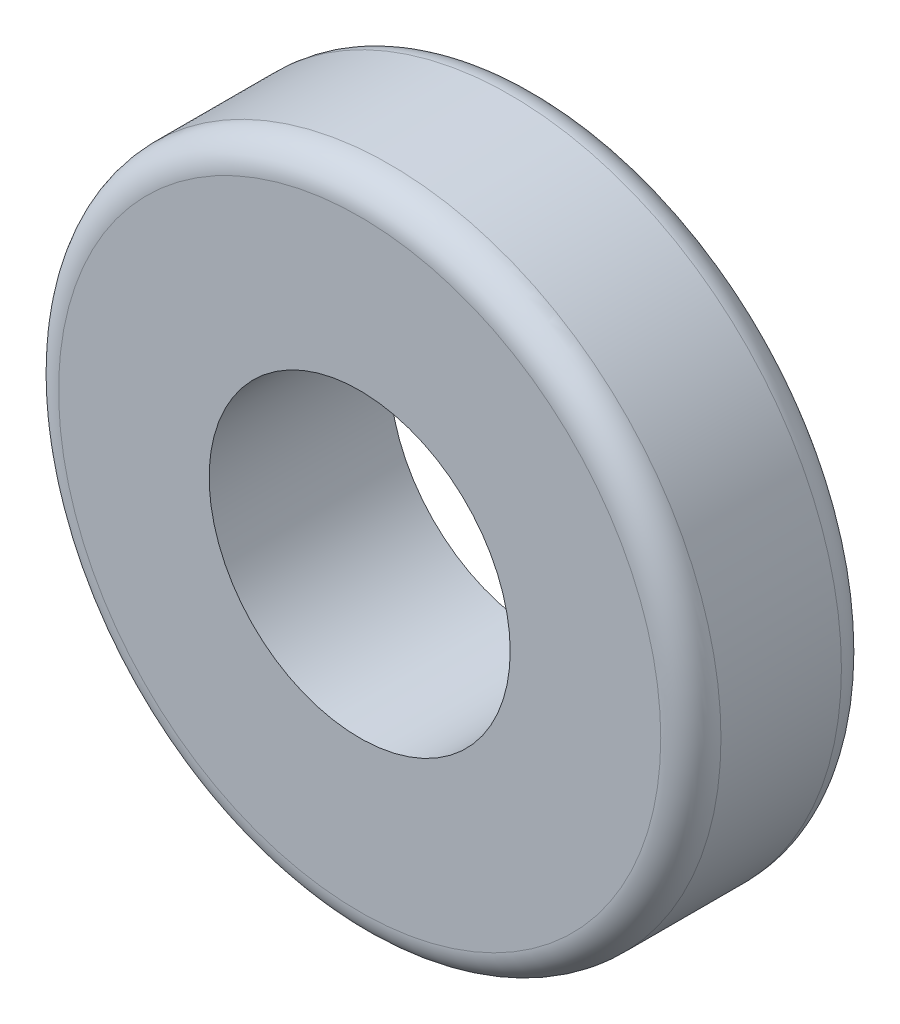
SolidWorks part; units mm, degrees
ref_plane "Alzado" through (0, 0, 0) normal (0, 0, 1) x (1, 0, 0)
ref_plane "Planta" through (0, 0, 0) normal (0, 1, 0) x (1, 0, 0)
ref_plane "Vista lateral" through (0, 0, 0) normal (1, 0, 0) x (0, 0, -1)
sketch "Croquis1" plane through (0, 0, 0) normal (0, 0, 1) x (1, 0, 0)
  circle A0 centre (0, 0) radius 5
  circle A1 centre (0, 0) radius 11
  dimension "D1" = 10
  dimension "D2" = 22
extrude "Saliente-Extruir1" add sketch "Croquis1" along normal blind 6
fillet "Redondeo1" radius 1 2 edges at (11, 0, 0) (11, 0, 6)
